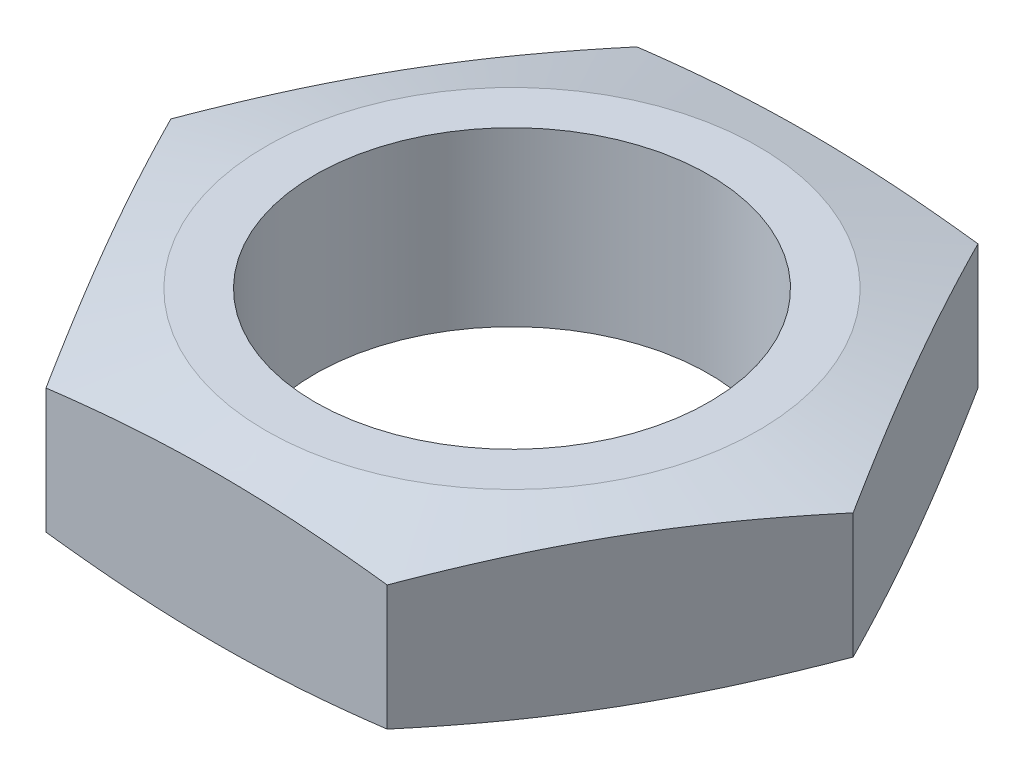
SolidWorks part; units mm, degrees
ref_plane "前视基准面" through (0, 0, 0) normal (0, 0, 1) x (1, 0, 0)
ref_plane "上视基准面" through (0, 0, 0) normal (0, 1, 0) x (1, 0, 0)
ref_plane "右视基准面" through (0, 0, 0) normal (1, 0, 0) x (0, 0, -1)
sketch "草图1" plane through (0, 0, 0) normal (0, 1, 0) x (1, 0, 0)
  line L1 (6.9282, 0) -> (3.4641, 6)
  line L2 (3.4641, 6) -> (-3.4641, 6)
  line L3 (-3.4641, 6) -> (-6.9282, 0)
  line L4 (-6.9282, 0) -> (-3.4641, -6)
  line L5 (-3.4641, -6) -> (3.4641, -6)
  line L6 (3.4641, -6) -> (6.9282, 0)
  circle A0 centre (0, 0) radius 4
  circle A1 centre (0, 0) radius 6 construction
  dimension "D2" = 8
  dimension "D1" = 12
extrude "凸台-拉伸1" add sketch "草图1" along normal blind 3.5
sketch "草图2" plane through (0, 0, 0) normal (1, 0, 0) x (0, 0, -1)
  line L0 (-5, 3.5) -> (-9, 3.5)
  line L1 (-6, 3.5) -> (0, 3.5) construction
  line L2 (-9, 3.5) -> (-9, 2.5)
  line L3 (-9, 2.5) -> (-5, 3.5)
  line L4 (-6, 1.75) -> (0, 1.75) construction
  line L5 (-6, 3.5) -> (-6, 0) construction
  line L6 (0, 3.5) -> (0, 0) construction
  line L7 (-9, 1) -> (-5, 0)
  line L8 (-9, 0) -> (-9, 1)
  line L9 (-5, 0) -> (-9, 0)
  dimension "D1" = 5
  dimension "D2" = 1
  dimension "D3" = 4
revolve "切除-旋转1" cut sketch "草图2" angle 360 about axis through (0, 3.5, 0) along (0, -1, 0)
